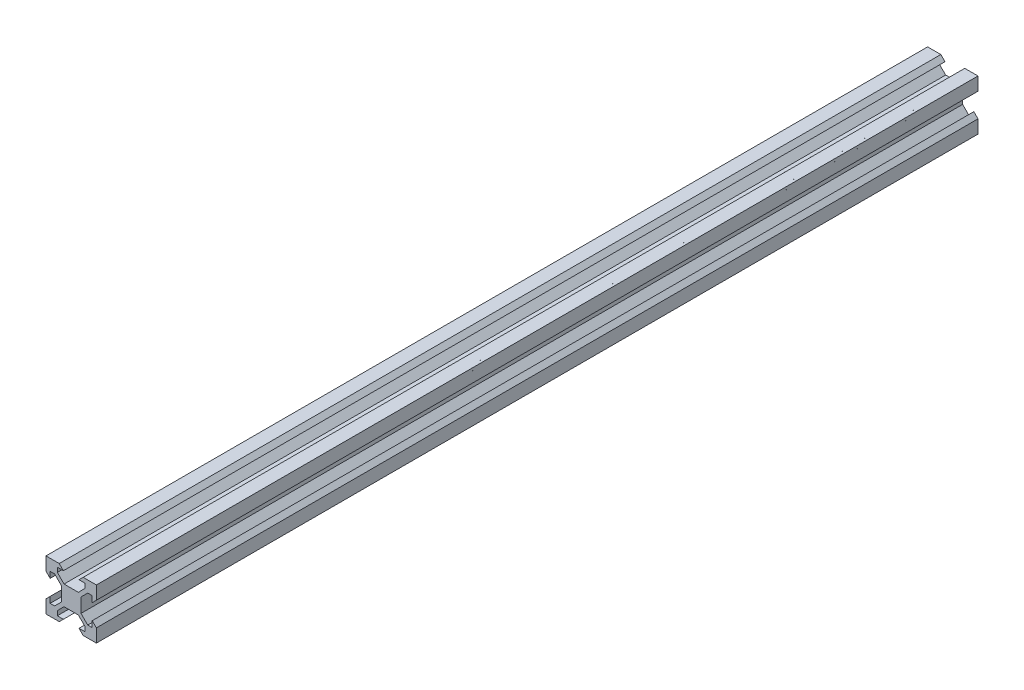
SolidWorks part; units mm, degrees
ref_plane "Front Plane" through (0, 0, 0) normal (0, 0, 1) x (1, 0, 0)
ref_plane "Top Plane" through (0, 0, 0) normal (0, 1, 0) x (1, 0, 0)
ref_plane "Right Plane" through (0, 0, 0) normal (1, 0, 0) x (0, 0, -1)
sketch "Sketch1" plane through (0, 0, 0) normal (0, 0, 1) x (1, 0, 0)
  line L88 (2.8343, 3.894) -> (-2.8343, 3.894)
  line L89 (-2.8343, 3.894) -> (-5.5, 6.5588)
  line L90 (-5.5, 6.5588) -> (-5.5, 8.3491)
  line L91 (-5.5, 8.3491) -> (-3.1, 8.3491)
  line L92 (-3.1, 8.3491) -> (-4.75, 9.9986)
  line L93 (-4.75, 9.9986) -> (-10, 9.9986)
  line L94 (-10, 9.9986) -> (-10, 4.747)
  line L95 (-10, 4.747) -> (-8.35, 3.0975)
  line L96 (-8.35, 3.0975) -> (-8.3507, 5.4975)
  line L97 (-8.3507, 5.4975) -> (-6.5605, 5.498)
  line L98 (-6.5605, 5.498) -> (-3.8948, 2.8332)
  line L99 (-3.8948, 2.8332) -> (-3.8948, -2.8332)
  line L100 (-3.8948, -2.8332) -> (-6.5605, -5.498)
  line L101 (-6.5605, -5.498) -> (-8.3507, -5.4975)
  line L102 (-8.3507, -5.4975) -> (-8.35, -3.0975)
  line L103 (-8.35, -3.0975) -> (-10, -4.747)
  line L104 (-10, -4.747) -> (-10, -9.9986)
  line L105 (-10, -9.9986) -> (-4.75, -9.9986)
  line L106 (-4.75, -9.9986) -> (-3.1, -8.3491)
  line L107 (-3.1, -8.3491) -> (-5.5, -8.3491)
  line L108 (-5.5, -8.3491) -> (-5.5, -6.5588)
  line L109 (-5.5, -6.5588) -> (-2.8343, -3.894)
  line L110 (-2.8343, -3.894) -> (2.8343, -3.894)
  line L111 (2.8343, -3.894) -> (5.5, -6.5588)
  line L112 (5.5, -6.5588) -> (5.5, -8.3491)
  line L113 (5.5, -8.3491) -> (3.1, -8.3491)
  line L114 (3.1, -8.3491) -> (4.75, -9.9986)
  line L115 (4.75, -9.9986) -> (10, -9.9986)
  line L116 (10, -9.9986) -> (10, -4.747)
  line L117 (10, -4.747) -> (8.35, -3.0975)
  line L118 (8.35, -3.0975) -> (8.3507, -5.4975)
  line L119 (8.3507, -5.4975) -> (6.5605, -5.498)
  line L120 (6.5605, -5.498) -> (3.8948, -2.8332)
  line L121 (3.8948, -2.8332) -> (3.8948, 2.8332)
  line L122 (3.8948, 2.8332) -> (6.5605, 5.498)
  line L123 (6.5605, 5.498) -> (8.3507, 5.4975)
  line L124 (8.3507, 5.4975) -> (8.35, 3.0975)
  line L125 (8.35, 3.0975) -> (10, 4.747)
  line L126 (10, 4.747) -> (10, 9.9986)
  line L127 (10, 9.9986) -> (4.75, 9.9986)
  line L128 (4.75, 9.9986) -> (3.1, 8.3491)
  line L129 (3.1, 8.3491) -> (5.5, 8.3491)
  line L130 (5.5, 8.3491) -> (5.5, 6.5588)
  line L131 (5.5, 6.5588) -> (2.8343, 3.894)
  dimension "D2" = 5.25
  dimension "D3" = 19.9971
  dimension "D4" = 20
extrude "Boss-Extrude1" add sketch "Sketch1" along normal blind 350
